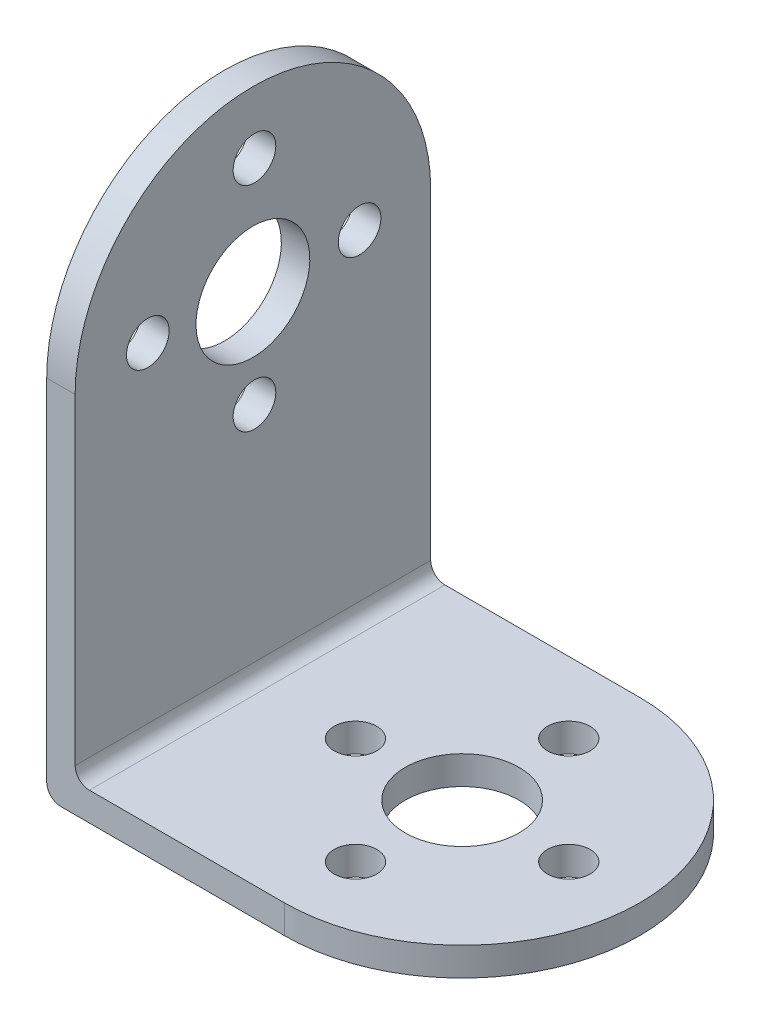
SolidWorks part; units mm, degrees
material "1060 Alloy"
ref_plane "Front Plane" through (0, 0, 0) normal (0, 0, 1) x (1, 0, 0)
ref_plane "Top Plane" through (0, 0, 0) normal (0, 1, 0) x (1, 0, 0)
ref_plane "Right Plane" through (0, 0, 0) normal (1, 0, 0) x (0, 0, -1)
sketch "Sketch1" plane through (0, 0, 0) normal (0, 0, 1) x (1, 0, 0)
  line L0 (2, 38.1) -> (2, 0)
  line L1 (0, 0) -> (29.21, 0)
  line L2 (0, 0) -> (0, 38.1)
  line L3 (0, 38.1) -> (29.21, 38.1)
  line L4 (29.21, 0) -> (29.21, 38.1)
  line L5 (2, 2) -> (29.21, 2)
  dimension "D1" = 38.1
  dimension "D2" = 29.21
  dimension "D3" = 2
  dimension "D4" = 2
extrude "Boss-Extrude1" add sketch "Sketch1" along normal blind 25 contours L3 L2 L1 L0 | L5 L0 L1 L4
sketch "Sketch2" plane through (0, 2, 0) normal (0, 1, 0) x (1, 0, 0)
  line L0 (2, -25) -> (29.21, -25) construction
  line L1 (29.21, 0) -> (4.21, 0)
  line L2 (29.21, 0) -> (29.21, -25)
  line L3 (29.21, -25) -> (4.21, -25)
  line L4 (4.21, 0) -> (4.21, -25)
  line L5 (4.21, 0) -> (29.21, -25) construction
  line L6 (4.21, -25) -> (29.21, 0) construction
  circle A0 centre (16.71, -12.5) radius 12.5
  circle A1 centre (16.71, -12.5) radius 4
  circle A2 centre (16.71, -12.5) radius 7.5 construction
  circle A3 centre (24.21, -12.5) radius 1.5
  circle A4 centre (16.71, -20) radius 1.5
  circle A5 centre (9.21, -12.5) radius 1.5
  circle A6 centre (16.71, -5) radius 1.5
  point P22 (16.71, -12.5)
  line M1 (29.21, 0) -> (2, 0)
  line M4 (29.21, -25) -> (29.21, 0)
  dimension "D2" = 25
  dimension "D3" = 8
  dimension "D4" = 3
  dimension "D6" = 15
  dimension "D1" = 25
  dimension "D5" = 4
extrude "Cut-Extrude1" cut sketch "Sketch2" against normal blind 25 contours A4 | A5 | A6 | A3 | A1 | A0 L2 M1 | A0 L3 M4
sketch "Sketch3" plane through (2, 0, 0) normal (1, 0, 0) x (0, 0, -1)
  line L0 (-12.5, 38.1) -> (-12.5, 2) construction
  line L1 (-25, 38.1) -> (0, 38.1) construction
  line L2 (-25, 2) -> (0, 2) construction
  line L3 (0, 38.1) -> (-25, 38.1)
  line L4 (0, 38.1) -> (0, 13.1)
  line L5 (0, 13.1) -> (-25, 13.1)
  line L6 (-25, 38.1) -> (-25, 13.1)
  line L7 (-25, 38.1) -> (0, 13.1) construction
  line L8 (-25, 13.1) -> (0, 38.1) construction
  line L9 (0, 38.1) -> (0, 2) construction
  line L10 (-25, 38.1) -> (-25, 2) construction
  circle A0 centre (-12.5, 25.6) radius 12.5
  circle A1 centre (-12.5, 25.6) radius 4
  circle A2 centre (-12.5, 25.6) radius 7.5 construction
  circle A3 centre (-5, 25.6) radius 1.5
  circle A4 centre (-12.391, 18.684) radius 1.5
  circle A5 centre (-19.891, 26.184) radius 1.5
  circle A6 centre (-12.391, 33.684) radius 1.5
  point P22 (-12.391, 26.184)
  line M2 (0, 38.1) -> (-25, 38.1)
  line M3 (-25, 38.1) -> (-25, 2)
  dimension "D1" = 0
  dimension "D2" = 25
  dimension "D3" = 0
  dimension "D4" = 0
extrude "Cut-Extrude3" cut sketch "Sketch3" against normal blind 25 contours A0 L3 M3 | A0 L4 M2 | A6 | A3 | A5 | A1 | A4
fillet "Fillet1" radius 1 2 edges at (0, 0, 12.5) (2, 2, 12.5)
